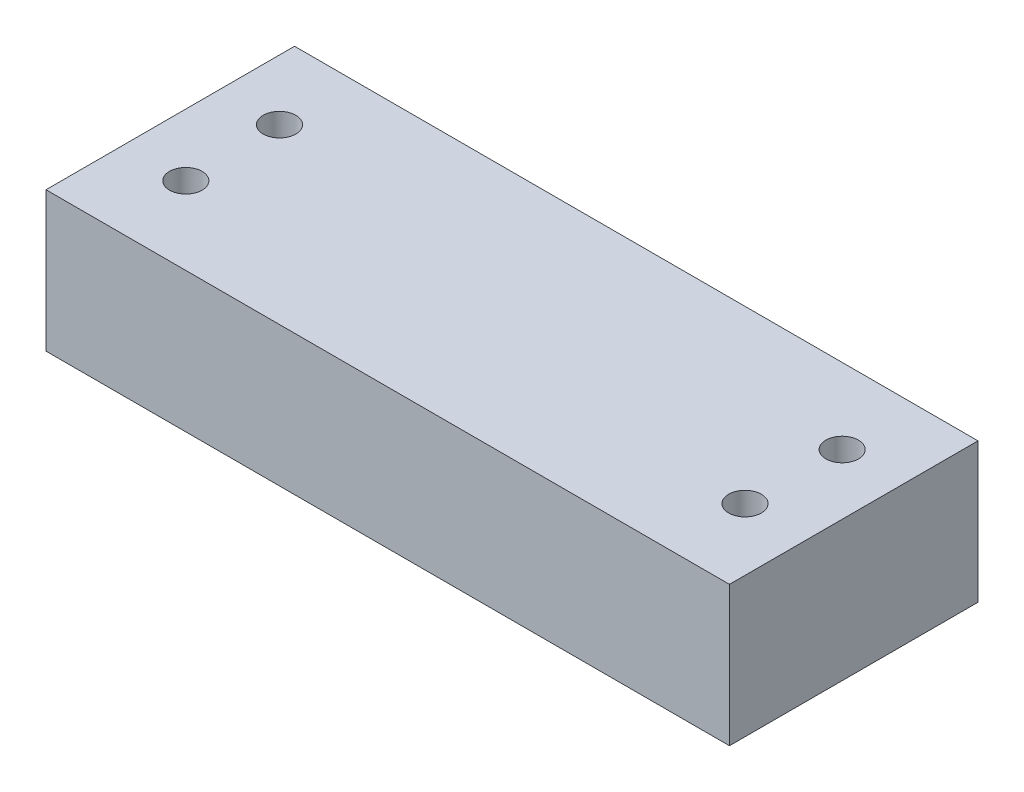
SolidWorks part; units mm, degrees
ref_plane "Front Plane" through (0, 0, 0) normal (0, 0, 1) x (1, 0, 0)
ref_plane "Top Plane" through (0, 0, 0) normal (0, 1, 0) x (1, 0, 0)
ref_plane "Right Plane" through (0, 0, 0) normal (1, 0, 0) x (0, 0, -1)
sketch "Sketch2" plane through (0, 0, 0) normal (0, 1, 0) x (1, 0, 0)
  line L1 (44, -16) -> (-44, -16)
  line L2 (44, -16) -> (44, 16)
  line L3 (44, 16) -> (-44, 16)
  line L4 (-44, -16) -> (-44, 16)
  line L5 (44, -16) -> (-44, 16) construction
  line L6 (44, 16) -> (-44, -16) construction
  point P0 (0, 0)
  dimension "D1" = 88
  dimension "D2" = 32
extrude "Boss-Extrude1" add sketch "Sketch2" along normal blind 18
hole_wizard "M5 Tapped Hole1" positions "Sketch3" profile "Sketch4" tap size "M5" standard "ISO" end condition through all
sketch "Sketch3" plane through (0, 18, 0) normal (0, 1, 0) x (1, 0, 0)
  line L0 (44, -16) -> (44, 16) construction
  line L1 (-44, -16) -> (44, -16) construction
  line L2 (44, 0) -> (0, 0.7994) construction
  line L4 (0, 16) -> (0, -16) construction
  line L5 (44, 16) -> (-44, 16) construction
  point P0 (36, -6)
  point P12 (36.2232, 6.2866)
  point P19 (0, 0)
  point P20 (-36, -6)
  point P21 (-36.2232, 6.2866)
  dimension "D1" = 8
  dimension "D2" = 10
sketch "Sketch4" plane through (36, 18, 6) normal (1, 0, 0) x (0, 0, 1)
  line L0 (0, 0) -> (0, 18)
  line L1 (0, 18) -> (2.1, 18)
  line L2 (2.1, 18) -> (2.1, 0)
  line L5 (2.1, 0) -> (0, 0)
  line L11 (0, -6.35) -> (0, 107.95) construction
  dimension "Thread Major Dia." = 4.2
  dimension "Thru Tap Drill Depth" = 18
